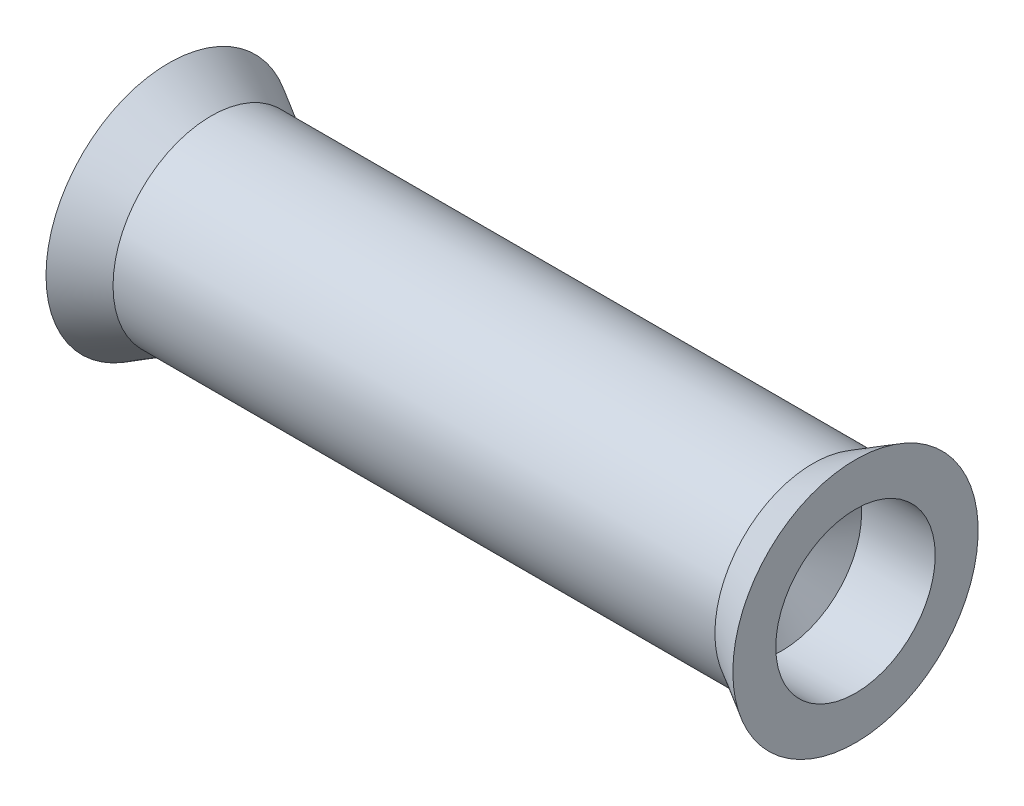
SolidWorks part; units mm, degrees
revolve "Cut-to-GripLength" cut sketch "Sketch2" angle 360 about L0
sketch "Sketch2" plane through (0, 0, 0) normal (0, 0, 1) x (1, 0, 0)
  line L0 (-30, 0) -> (30, 0) construction
  line L1 (-30, 0) -> (31, 0) construction
  line L3 (-16, 0) -> (-14, 0)
  line L4 (-16, 0) -> (-16, 5)
  line L5 (-16, 5) -> (-14, 5)
  line L6 (-14, 0) -> (-14, 5)
  line L7 (14, 0) -> (16, 0)
  line L8 (14, 0) -> (14, 5)
  line L9 (14, 5) -> (16, 5)
  line L10 (16, 0) -> (16, 5)
  dimension "GripLength" = 28
  dimension "D1" = 14
  dimension "D2" = 32
  dimension "D3" = 16
  dimension "D4" = 10
revolve "Base-Revolve" add sketch "Sketch1" angle 360 about L0
sketch "Sketch1" plane through (0, 0, 0) normal (0, 0, 1) x (1, 0, 0)
  line L0 (-30, 0) -> (31, 0) construction
  line L2 (-15, 0) -> (15, 0)
  line L3 (-15, 0) -> (-15, 4)
  line L4 (-15, 4) -> (15, 4)
  line L5 (15, 0) -> (15, 4)
  dimension "Length" = 30
  dimension "Diameter" = 8
material "Plain Carbon Steel"
ref_plane "Plane1" through (0, 0, 0) normal (0, 0, 1) x (1, 0, 0)
ref_plane "Plane2" through (0, 0, 0) normal (0, 1, 0) x (1, 0, 0)
ref_plane "Plane3" through (0, 0, 0) normal (1, 0, 0) x (0, 0, -1)
other "Configuration Table"
sketch "Sketch3" plane through (0, 0, 0) normal (0, 0, 1) x (1, 0, 0)
  line L0 (-23, 0) -> (23, 0) construction
  line L1 (-30, 0) -> (31, 0) construction
  line L2 (-15.5, 4) -> (-15.5, 0)
  line L3 (-15.5, 0) -> (-14, 0)
  line L4 (-15.5, 4) -> (-14, 5)
  line L5 (-14, 5) -> (-14, 0)
  line L6 (15.5, 4) -> (14, 5)
  line L7 (14, 5) -> (14, 0)
  line L10 (15.5, 4) -> (15.5, 0)
  line L11 (15.5, 0) -> (14, 0)
  line L12 (-14, 4) -> (-14, -4) construction
  line L13 (14, -4) -> (14, 4) construction
  dimension "D1" = 8
  dimension "D2" = 10
  dimension "D3" = 1.5
revolve "HeadTypeA" [suppressed] add sketch "Sketch3" angle 360 about L0
sketch "Sketch4" plane through (0, 0, 0) normal (0, 0, 1) x (1, 0, 0)
  line L0 (-20, 0) -> (20, 0) construction
  line L1 (-30, 0) -> (31, 0) construction
  line L2 (-14, 0) -> (-14, 5)
  line L3 (-14, 5) -> (-12.2679, 4)
  line L4 (-12.2679, 0) -> (-14, 0)
  line L5 (-14, -5) -> (-12.2679, -4) construction
  line L6 (0, 0) -> (0, 14) construction
  line L7 (12.2679, 0) -> (14, 0)
  line L8 (14, 0) -> (14, 5)
  line L9 (-12.2679, 4) -> (-12.2679, 0)
  line L10 (12.2679, 4) -> (12.2679, 0)
  line L11 (14, 5) -> (12.2679, 4)
  dimension "D1" = 8
  dimension "D2" = 10
  dimension "D3" = 60
  dimension "D4" = 28
revolve "HeadTypeB" add sketch "Sketch4" angle 360 about L0
sketch "Sketch5" plane through (0, 0, 0) normal (0, 0, 1) x (1, 0, 0)
  line L0 (-22, 0) -> (21, 0) construction
  line L1 (-30, 0) -> (31, 0) construction
  line L2 (-9.1236, 0) -> (-11, 3.25)
  line L4 (-11, 3.25) -> (-15, 3.25)
  line L5 (-15, 3.25) -> (-15, 0)
  line L6 (-15, 0) -> (-9.1236, 0)
  line L7 (9.1236, 0) -> (11, 3.25)
  line L8 (11, 3.25) -> (15, 3.25)
  line L9 (15, 3.25) -> (15, 0)
  line L10 (15, 0) -> (9.1236, 0)
  line L11 (-9.1236, 0) -> (-11, -3.25) construction
  line L12 (9.1236, 0) -> (11, -3.25) construction
  dimension "D1" = 30
  dimension "D2" = 15
  dimension "HoleDepth" = 4
  dimension "D3" = 4
  dimension "D4" = 120
  dimension "D5" = 120
  dimension "HoleDia" = 6.5
  dimension "D6" = 6.5
revolve "HoleTypeA" cut sketch "Sketch5" angle 360 about L0
sketch "Sketch6" plane through (0, 0, 0) normal (0, 0, 1) x (1, 0, 0)
  line L0 (-22, 0) -> (22, 0) construction
  line L1 (-30, 0) -> (31, 0) construction
  line L2 (-15, 4) -> (-12.6906, 0)
  line L4 (-12.6906, 0) -> (-15, 0)
  line L5 (-15, 0) -> (-15, 4)
  line L6 (-15, -4) -> (-12.6906, 0) construction
  line L7 (15, -4) -> (12.6906, 0) construction
  line L8 (12.6906, 0) -> (15, 0)
  line L9 (15, 0) -> (15, 4)
  line L10 (15, 4) -> (12.6906, 0)
  dimension "D1" = 120
  dimension "D2" = 8
  dimension "D3" = 120
  dimension "D4" = 30
  dimension "D5" = 15
revolve "HoleTypeB" [suppressed] cut sketch "Sketch6" angle 360 about L0
equation "\"D1@Sketch2\" = \"GripLength@Sketch2\" / 2"
equation "\"D2@Sketch2\" = \"Length@Sketch1\" + 2"
equation "\"D3@Sketch2\" = \"D2@Sketch2\" / 2"
equation "\"D4@Sketch2\" = \"Diameter@Sketch1\" + 2"
equation "\"D1@Sketch3\" = \"Diameter@Sketch1\""
equation "\"D2@Sketch3\" = \"Diameter@Sketch1\" * 1.25"
equation "\"D3@Sketch3\" = \"HeadHt@Sketch3\""
equation "\"D1@Sketch5\" = \"Length@Sketch1\""
equation "\"D2@Sketch5\" = \"D1@Sketch5\" / 2"
equation "\"D3@Sketch5\" = \"HoleDepth@Sketch5\""
equation "\"D5@Sketch5\" = \"D4@Sketch5\""
equation "\"D6@Sketch5\" = \"HoleDia@Sketch5\""
equation "\"D2@Sketch6\" = \"Diameter@Sketch1\""
equation "\"D3@Sketch6\" = \"D1@Sketch6\""
equation "\"D4@Sketch6\" = \"Length@Sketch1\""
equation "\"D5@Sketch6\" = \"D4@Sketch6\" / 2"
equation "\"D1@Sketch4\" = \"Diameter@Sketch1\""
equation "\"D2@Sketch4\" = \"Diameter@Sketch1\" * 1.25"
equation "\"D4@Sketch4\" = \"GripLength@Sketch2\""
